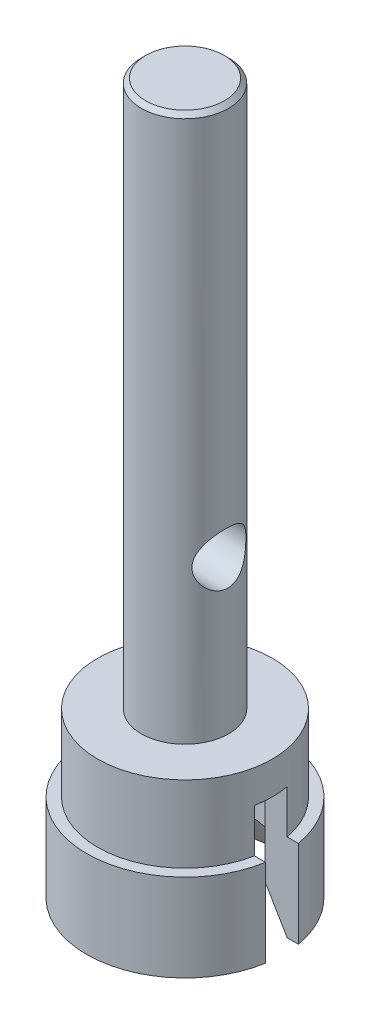
SolidWorks part; units mm, degrees
ref_plane "前视基准面" through (0, 0, 0) normal (0, 0, 1) x (1, 0, 0)
ref_plane "上视基准面" through (0, 0, 0) normal (0, 1, 0) x (1, 0, 0)
ref_plane "右视基准面" through (0, 0, 0) normal (1, 0, 0) x (0, 0, -1)
sketch "草图1" plane through (0, 0, 0) normal (0, 0, 1) x (1, 0, 0)
  line L0 (0, 0) -> (0, -34.1193) construction
  line L1 (0, 0) -> (-2, 0)
  line L2 (-2, 0) -> (-2, -25)
  line L3 (-2, -25) -> (-4, -25)
  line L4 (-4, -25) -> (-4, -28.5)
  line L5 (-4, -28.5) -> (-4.5, -28.5)
  line L6 (-4.5, -28.5) -> (-4.5, -32.5)
  line L7 (-4.5, -32.5) -> (0, -32.5)
  line L8 (0, -32.5) -> (0, 0)
  dimension "D1" = 32.5
  dimension "D2" = 4
  dimension "D3" = 3.5
  dimension "D4" = 4.5
  dimension "D5" = 4
  dimension "D6" = 2
revolve "旋转1" add sketch "草图1" angle 360 about L0
sketch "草图2" plane through (0, -32.5, 0) normal (0, -1, 0) x (1, 0, 0)
  circle A0 centre (0, 0) radius 3
  dimension "D1" = 6
extrude "切除-拉伸1" cut sketch "草图2" against normal blind 6
chamfer "倒角1" distance 1 angle 60 1 edges at (0, -32.5, -3)
sketch "草图3" plane through (0, -32.5, 0) normal (0, -1, 0) x (1, 0, 0)
  line L1 (-5.5, 0.75) -> (5.5, 0.75)
  line L2 (-5.5, 0.75) -> (-5.5, -0.75)
  line L3 (-5.5, -0.75) -> (5.5, -0.75)
  line L4 (5.5, 0.75) -> (5.5, -0.75)
  line L5 (-5.5, 0.75) -> (5.5, -0.75) construction
  line L6 (-5.5, -0.75) -> (5.5, 0.75) construction
  point P0 (0, 0)
  dimension "D1" = 1.5
  dimension "D2" = 11
extrude "切除-拉伸3" cut sketch "草图3" along direction (0, -1, 0) on the side against the normal up to surface (6 mm away)
chamfer "倒角2" distance 0.2 angle 45 1 edges at (0, 0, 2)
hole_wizard "M2 间隙孔1" positions "3D草图1" profile "草图4" hole size "M2" standard "GB"
sketch3d "3D草图1"
  line L0 (-1.9991, -18, -0.0602) -> (-3.9995, -26.5, -0.0602) construction
  arc A0 (-3.9291, -26.5, -0.75) -> (-3.9291, -26.5, 0.75) centre (0, -26.5, 0) ccw construction
  point P0 (-1.9991, -18, -0.0602)
  point P8 (0, -22.5, 0)
  dimension "D1" = 7
sketch "草图4" plane through (-1.9991, -18, -0.0602) normal (0, 1, 0) x (-0.0301, 0, 0.9995)
  line L0 (0, 0) -> (0, 10.721)
  line L1 (0, 10.721) -> (1.2, 10)
  line L2 (1.2, 10) -> (1.2, 0)
  line L5 (1.2, 0) -> (0, 0)
  line L10 (0, 10.721) -> (-1.2, 10) construction
  line L11 (0, -6.35) -> (0, 107.95) construction
  dimension "孔直径" = 2.4
  dimension "孔深度" = 10
  dimension "导头角度" = 118
